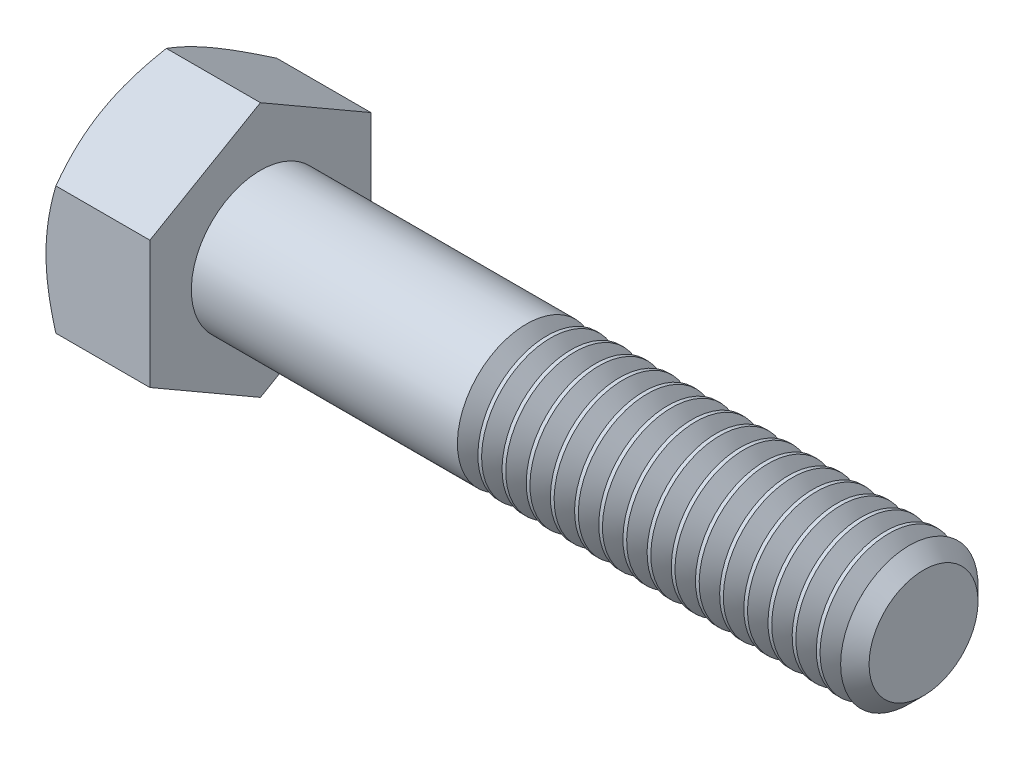
SolidWorks part; units mm, degrees
extrude "BaseHead" add sketch "Sketch1" along normal blind 5.969
sketch "Sketch1" plane through (0, 0, 0) normal (1, 0, 0) x (0, 0, -1)
  line L0 (6.35, 3.6662) -> (6.35, -3.6662)
  line L1 (-6.35, 3.6662) -> (-6.35, -3.6662)
  line L2 (6.35, -3.6662) -> (0, -7.3323)
  line L3 (0, -7.3323) -> (-6.35, -3.6662)
  line L4 (6.35, 3.6662) -> (0, 7.3323)
  line L5 (0, 7.3323) -> (-6.35, 3.6662)
  dimension "Width_flats" = 12.7
  dimension "D2" = 120
  dimension "D3" = 6.35
  dimension "D4" = 6.35
  dimension "D5" = 6.35
ref_plane "Plane1" through (0, 0, 0) normal (0, 0, 1) x (1, 0, 0)
ref_plane "Plane2" through (0, 0, 0) normal (0, 1, 0) x (1, 0, 0)
ref_plane "Plane3" through (0, 0, 0) normal (1, 0, 0) x (0, 0, -1)
other "Configuration Table"
sketch "BodySke" plane through (0, 0, 0) normal (0, 0, 1) x (1, 0, 0)
  line L0 (0, 3.6662) -> (0, -3.6662) construction
  line L1 (0, 0) -> (44.069, 0)
  line L2 (0, 0) -> (0, 3.9688)
  line L3 (0, 3.9688) -> (43.2295, 3.9688)
  line L4 (44.069, 0) -> (44.069, 3.1293)
  line L5 (5.969, 7.3323) -> (5.969, 3.6662) construction
  line L6 (44.069, 3.1293) -> (43.2295, 3.9688)
  line L7 (0, 0) -> (96.52, 0) construction
  line L8 (44.069, -3.1293) -> (43.2295, -3.9688) construction
  line L9 (0, -3.9688) -> (43.2295, -3.9688) construction
  line L10 (7.3787, 15.24) -> (7.3787, -2.54) construction
  line L11 (21.844, 15.24) -> (21.844, -2.54) construction
  line L12 (5.969, 3.6662) -> (5.969, -3.6662) construction
  dimension "Diameter" = 7.9375
revolve "BaseBody" add sketch "BodySke" angle 360 about L7
cosmetic thread "ThreadCosmetic" [suppressed] parameters "Thread_length"=22.225, "Thread_minor"=6.2586
sketch "Sketch3" plane through (0, 0, 0) normal (0, 0, 1) x (1, 0, 0)
  line L0 (0, 6.35) -> (4.2333, 13.6823)
  line L1 (0, 7.3323) -> (0, 3.6662) construction
  line L2 (4.2333, 13.6823) -> (4.2333, 20.0323)
  line L3 (4.2333, 20.0323) -> (-12.7, 20.0323)
  line L4 (-12.7, 20.0323) -> (-12.7, 6.35)
  line L5 (-12.7, 6.35) -> (0, 6.35)
  line L6 (0, 0) -> (99.06, 0) construction
  line L7 (5.969, 7.3323) -> (0, 7.3323) construction
  dimension "D4" = 6.35
  dimension "D1" = 6.35
  dimension "D2" = 6.35
  dimension "D3" = 12.7
  dimension "Head_ch_ang" = 30
revolve "HeadChamfer" cut sketch "Sketch3" angle 360 about L6
fillet "HeadFillet" [suppressed] radius 0.762
sketch "ThdSchSke" plane through (0, 0, 0) normal (0, 0, 1) x (1, 0, 0)
  line L0 (21.844, -3.1293) -> (21.2562, -3.9688)
  line L1 (21.844, -3.1293) -> (22.4318, -3.9688)
  line L2 (22.4318, -3.9688) -> (22.4318, -4.9609)
  line L3 (-3.175, 0) -> (5.1513, 0) construction
  line L5 (22.4318, -4.9609) -> (21.2562, -4.9609)
  line L6 (21.2562, -4.9609) -> (21.2562, -3.9688)
  dimension "Thread_minor" = 6.2586
  dimension "Diameter" = 7.9375
  dimension "Start" = 21.844
revolve "ThreadSchematic" cut sketch "ThdSchSke" angle 360 about L3
pattern_linear "ThdSchPat" count 16 spacing 1.3891 along (1, 0, 0) of "ThreadSchematic"
equation "\"D3@Sketch1\" = \"Width_flats@Sketch1\" / 2"
equation "\"D4@Sketch1\" = \"D3@Sketch1\""
equation "\"D5@Sketch1\" = \"D4@Sketch1\""
equation "\"Thread_minor@ThreadCosmetic\" = \"Minor_dia@BodySke\""
equation "\"D1@Sketch3\" = \"Width_flats@Sketch1\" / 2"
equation "\"Thread_length@ThreadCosmetic\" = ((sgn( (\"Length@BodySke\" - \"Advance@BodySke\" ) - \"Thread_nom@BodySke\" )-1)*( (\"Length@BodySke\" - \"Advance@BodySke\" ) - \"Thread_nom@BodySke\" ))/-2+ \"Thread_nom@BodySke\""
equation "\"Thread_minor@ThdSchSke\" = \"Minor_dia@BodySke\""
equation "\"Diameter@ThdSchSke\" = \"Diameter@BodySke\""
equation "\"Overcut@ThdSchSke\" = \"Diameter@BodySke\" * 1.25"
equation "\"Start@ThdSchSke\" = \"Head_ht@BaseHead\" + \"Length@BodySke\" - \"Thread_length@ThreadCosmetic\"  '---Non-countersunk---"
equation "\"Num_threads@ThdSchPat\" = int( \"Thread_length@ThreadCosmetic\" / \"Advance@BodySke\" + 0.999 )  + 1"
equation "\"Advance@ThdSchPat\" = \"Thread_length@ThreadCosmetic\" /  (\"Num_threads@ThdSchPat\" - 1) 'relax it"
equation "\"Num_threads@ThdSchPat\" = \"Num_threads@ThdSchPat\" - sgn( \"Num_threads@ThdSchPat\" - 1) '---chamfered tips only---"
